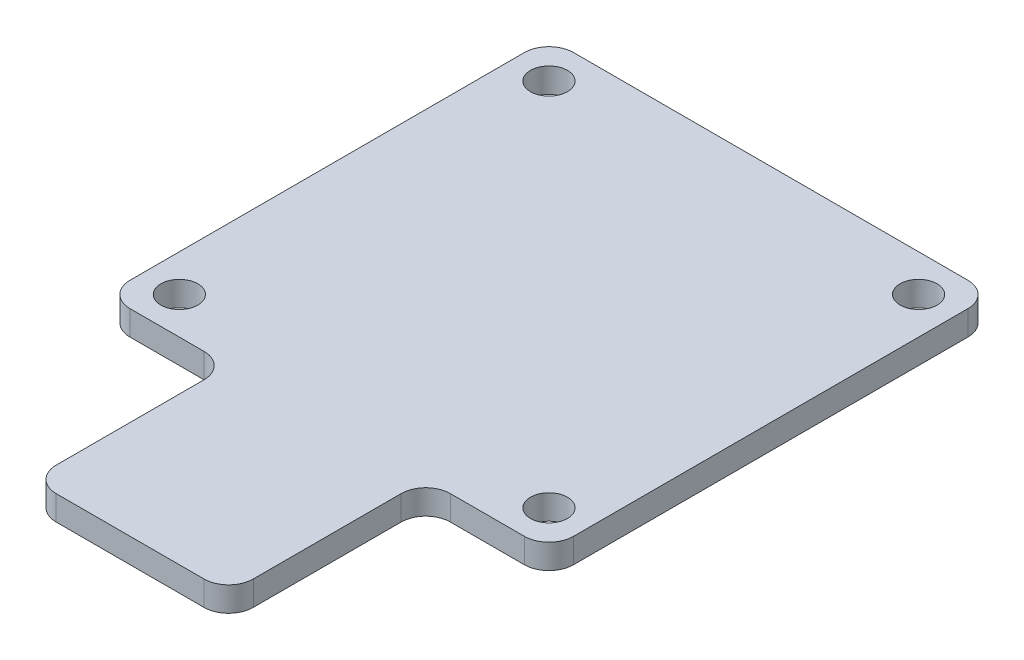
SolidWorks part; units mm, degrees
ref_plane "Front Plane" through (0, 0, 0) normal (0, 0, 1) x (1, 0, 0)
ref_plane "Top Plane" through (0, 0, 0) normal (0, 1, 0) x (1, 0, 0)
ref_plane "Right Plane" through (0, 0, 0) normal (1, 0, 0) x (0, 0, -1)
sketch "Sketch1" plane through (0, 0, 0) normal (0, 1, 0) x (1, 0, 0)
  line L0 (-18, 0) -> (18, 0) construction
  line L1 (-18, 18) -> (18, 18)
  line L2 (-18, 18) -> (-18, -18)
  line L3 (-18, -18) -> (-8, -18)
  line L4 (18, 18) -> (18, -18)
  line L5 (-18, 18) -> (18, -18) construction
  line L6 (-18, -18) -> (18, 18) construction
  line L7 (-15, 15) -> (15, 15) construction
  line L8 (-15, 15) -> (-15, -15) construction
  line L9 (-15, -15) -> (15, -15) construction
  line L10 (15, 15) -> (15, -15) construction
  line L11 (-15, 15) -> (15, -15) construction
  line L12 (-15, -15) -> (15, 15) construction
  line L13 (0, 18) -> (0, -18) construction
  line L14 (8, -34) -> (-8, -34)
  line L15 (-8, -34) -> (-8, -18)
  line L16 (8, -34) -> (8, -18)
  line L17 (8, -18) -> (18, -18)
  circle A0 centre (-15, 15) radius 1.5
  circle A1 centre (15, 15) radius 1.5
  circle A2 centre (15, -15) radius 1.5
  circle A3 centre (-15, -15) radius 1.5
  point P0 (0, 0)
  point P6 (0, 0)
  point P21 (0, -34)
  dimension "D5" = 3
  dimension "D1" = 36
  dimension "D2" = 36
  dimension "D3" = 30
  dimension "D4" = 30
  dimension "D6" = 8
  dimension "D7" = 52
extrude "Boss-Extrude1" add sketch "Sketch1" along normal blind 2
fillet "Fillet1" radius 2 8 edges at (-18, 1, -18) (18, 1, -18) (18, 1, 18) (8, 1, 18) (8, 1, 34) (-8, 1, 34) (-8, 1, 18) (-18, 1, 18)
